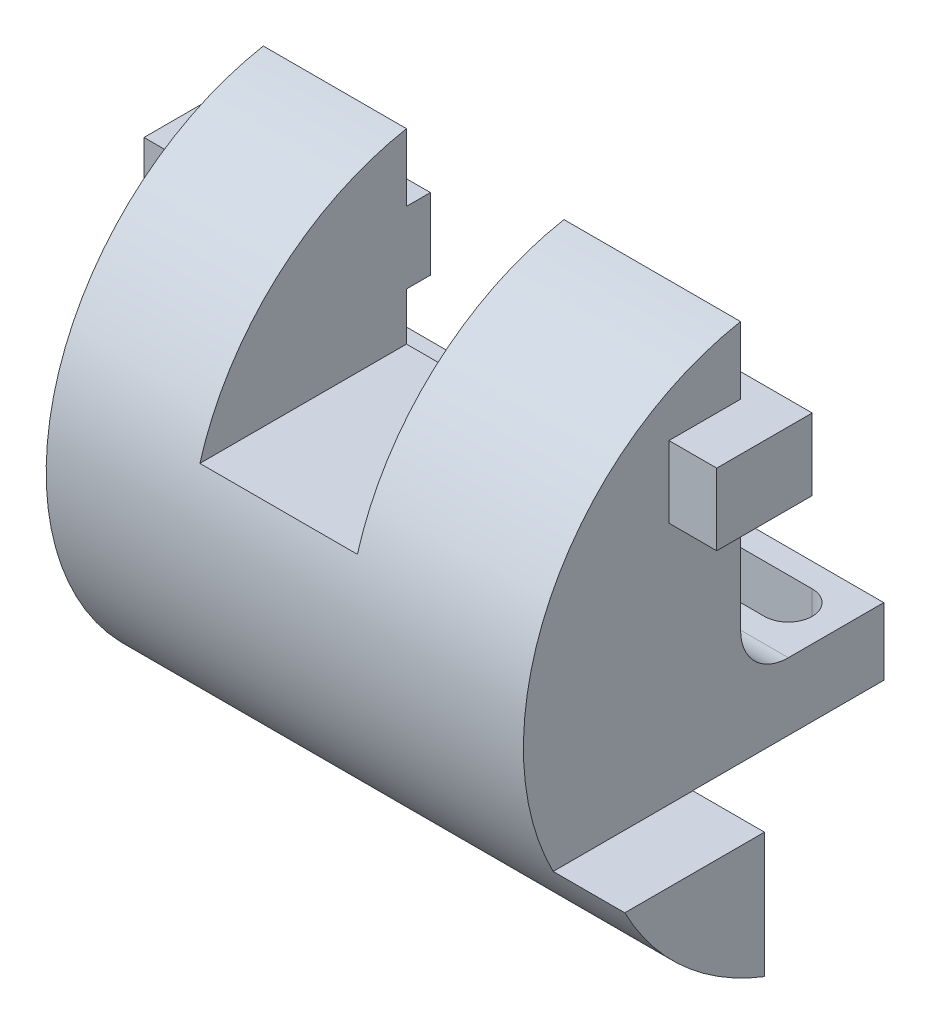
SolidWorks part; units mm, degrees
material "1060 Alloy"
ref_plane "Front Plane" through (0, 0, 0) normal (0, 0, 1) x (1, 0, 0)
ref_plane "Top Plane" through (0, 0, 0) normal (0, 1, 0) x (1, 0, 0)
ref_plane "Right Plane" through (0, 0, 0) normal (1, 0, 0) x (0, 0, -1)
sketch "Sketch3" plane through (0, 0, 0) normal (1, 0, 0) x (0, 0, -1)
  line L0 (0, -0.8989) -> (0, -47.819) construction
  line L1 (-44.557, -3.3887) -> (49.1139, -3.3887) construction
  line L2 (20, -35.7673) -> (20, -49.8722)
  line L3 (20, -35.7673) -> (0, -35.7673)
  line L6 (-10, -25.7673) -> (-10, 30.2327)
  line L7 (20, -49.8722) -> (-20, -49.8722)
  line L8 (-20, -49.8722) -> (-20, -76.1301)
  line L9 (20, -49.8722) -> (20, -44.8722) construction
  line L10 (20, -44.8722) -> (-55.3169, -28.8631) construction
  arc A0 (-10, 30.2327) -> (-20, -76.1301) centre (0, -24.359) ccw
  arc A1 (0, -35.7673) -> (-10, -25.7673) centre (0, -25.7673) cw
  dimension "D4" = 10
  dimension "D6" = 55.5
  dimension "D1" = 10
  dimension "D2" = 20
  dimension "D3" = 20
  dimension "D5" = 66
  dimension "D7" = 5
  dimension "D8" = 78
extrude "Boss-Extrude1" add sketch "Sketch3" along normal blind 115
sketch "Sketch4" plane through (115, 0, 0) normal (1, 0, 0) x (0, 0, -1)
  line L0 (-65.4024, 30.2327) -> (45.4024, 30.2327)
  line L3 (-65.4024, 30.2327) -> (-65.4024, -49.9185)
  line L4 (-65.4024, -49.9185) -> (45.4024, -49.9185)
  line L5 (45.4024, 30.2327) -> (45.4024, -49.9185)
  point P1 (-10, 30.2327)
extrude "Cut-Extrude1" cut sketch "Sketch4" against normal blind 15
ref_plane "Plane1" through (0, 31.141, 0) normal (0, 1, 0) x (1, 0, 0)
sketch "Sketch6" plane through (0, 31.141, 0) normal (0, 1, 0) x (1, 0, 0)
  line L0 (100, -10) -> (0, -10) construction
  line L1 (30, -10) -> (63, -10)
  line L2 (30, -10) -> (30, -55.5)
  line L3 (30, -55.5) -> (63, -55.5)
  line L4 (63, -10) -> (63, -55.5)
  line L5 (0, -55.5) -> (100, -55.5) construction
  dimension "D1" = 30
  dimension "D2" = 33
extrude "Cut-Extrude2" cut sketch "Sketch6" against normal blind 40
ref_plane "Plane2" through (0, 31.141, 0) normal (0, 1, 0) x (1, 0, 0)
sketch "Sketch9" plane through (0, -35.7673, 0) normal (0, 1, 0) x (1, 0, 0)
  line L0 (90, 10) -> (10, 10) construction
  line L1 (90, 5) -> (10, 5)
  line L2 (90, 15) -> (10, 15)
  arc A0 (90, 5) -> (90, 15) centre (90, 10) ccw
  arc A1 (10, 15) -> (10, 5) centre (10, 10) ccw
  point P2 (50, 10)
  dimension "D4" = 5
  dimension "D1" = 10
  dimension "D2" = 80
  dimension "D3" = 10
extrude "Cut-Extrude3" cut sketch "Sketch9" against normal through all
ref_plane "Plane3" through (0, 1.141, 0) normal (0, 1, 0) x (1, 0, 0)
sketch "Sketch10" plane through (0, 1.141, 0) normal (0, 1, 0) x (1, 0, 0)
  line L0 (63, -10) -> (63, -53.2917) construction
  line L1 (63, -25) -> (110, -25)
  line L2 (63, -25) -> (63, -5)
  line L3 (63, -5) -> (110, -5)
  line L4 (110, -25) -> (110, -5)
  line L5 (30, -10) -> (30, -53.2917) construction
  line L6 (30, -25) -> (-10, -25)
  line L7 (30, -25) -> (30, -5)
  line L8 (30, -5) -> (-10, -5)
  line L9 (-10, -25) -> (-10, -5)
  line L10 (100, -55.5) -> (100, -10) construction
  line L11 (100, -10) -> (63, -10) construction
  line L12 (100, -10) -> (0, -10) construction
  line L13 (0, -10) -> (0, -55.5) construction
  dimension "D1" = 10
  dimension "D2" = 5
  dimension "D3" = 20
  dimension "D4" = 5
  dimension "D5" = 20
  dimension "D6" = 10
extrude "Boss-Extrude2" add sketch "Sketch10" along normal blind 15
equation "\"A\"= 50.00"
equation "\"B\"= 55.00"
equation "\"C\"= 35.00"
